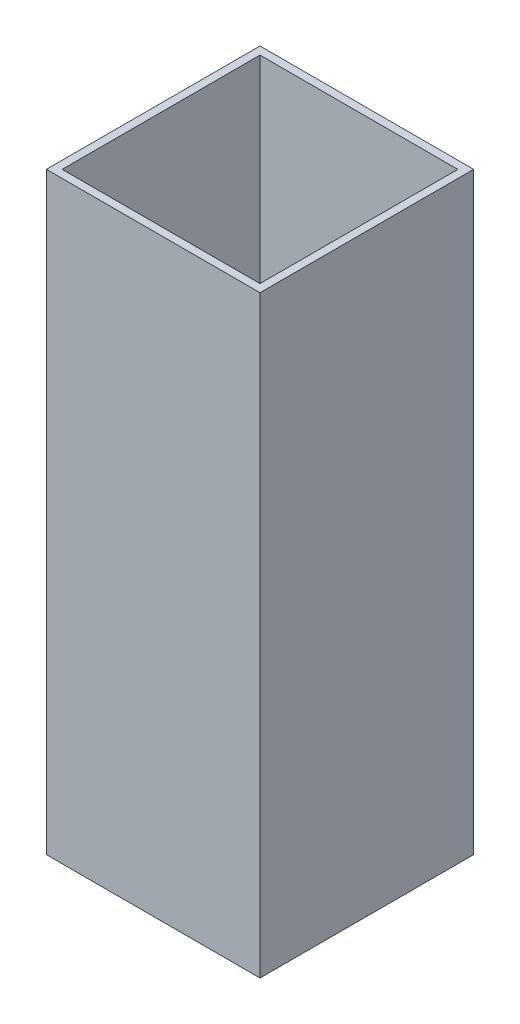
SolidWorks part; units mm, degrees
ref_plane "Front" through (0, 0, 0) normal (0, 0, 1) x (1, 0, 0)
ref_plane "Top" through (0, 0, 0) normal (0, 1, 0) x (1, 0, 0)
ref_plane "Right" through (0, 0, 0) normal (1, 0, 0) x (0, 0, -1)
sketch "Sketch1" plane through (0, 0, 0) normal (0, 1, 0) x (1, 0, 0)
  line L1 (13.5, -13.5) -> (-13.5, -13.5)
  line L2 (13.5, -13.5) -> (13.5, 13.5)
  line L3 (13.5, 13.5) -> (-13.5, 13.5)
  line L4 (-13.5, -13.5) -> (-13.5, 13.5)
  line L5 (13.5, -13.5) -> (-13.5, 13.5) construction
  line L6 (13.5, 13.5) -> (-13.5, -13.5) construction
  point P0 (0, 0)
  dimension "D1" = 27
  dimension "D2" = 27
extrude "Boss-Extrude2" add sketch "Sketch1" along normal blind 75
shell "Shell1" thickness 1
scale "Scale1" scale about origin uniform scaling yes scale factor 5
